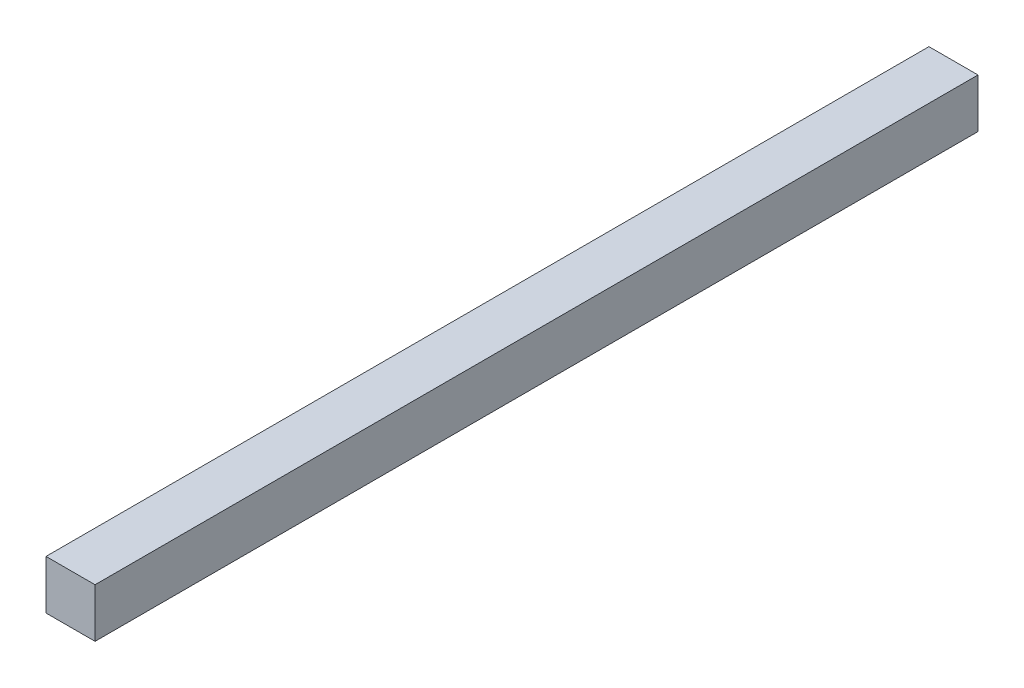
SolidWorks part; units mm, degrees
ref_plane "Front Plane" through (0, 0, 0) normal (0, 0, 1) x (1, 0, 0)
ref_plane "Top Plane" through (0, 0, 0) normal (0, 1, 0) x (1, 0, 0)
ref_plane "Right Plane" through (0, 0, 0) normal (1, 0, 0) x (0, 0, -1)
sketch "Sketch1" plane through (0, 0, 0) normal (0, 0, 1) x (1, 0, 0)
  line L1 (0, 0) -> (25.4, 0)
  line L2 (0, 0) -> (0, -25.4)
  line L3 (0, -25.4) -> (25.4, -25.4)
  line L4 (25.4, 0) -> (25.4, -25.4)
  dimension "D1" = 25.4
  dimension "D2" = 25.4
extrude "Boss-Extrude1" add sketch "Sketch1" along normal blind 457.2 contours L1 L4 L3 L2
